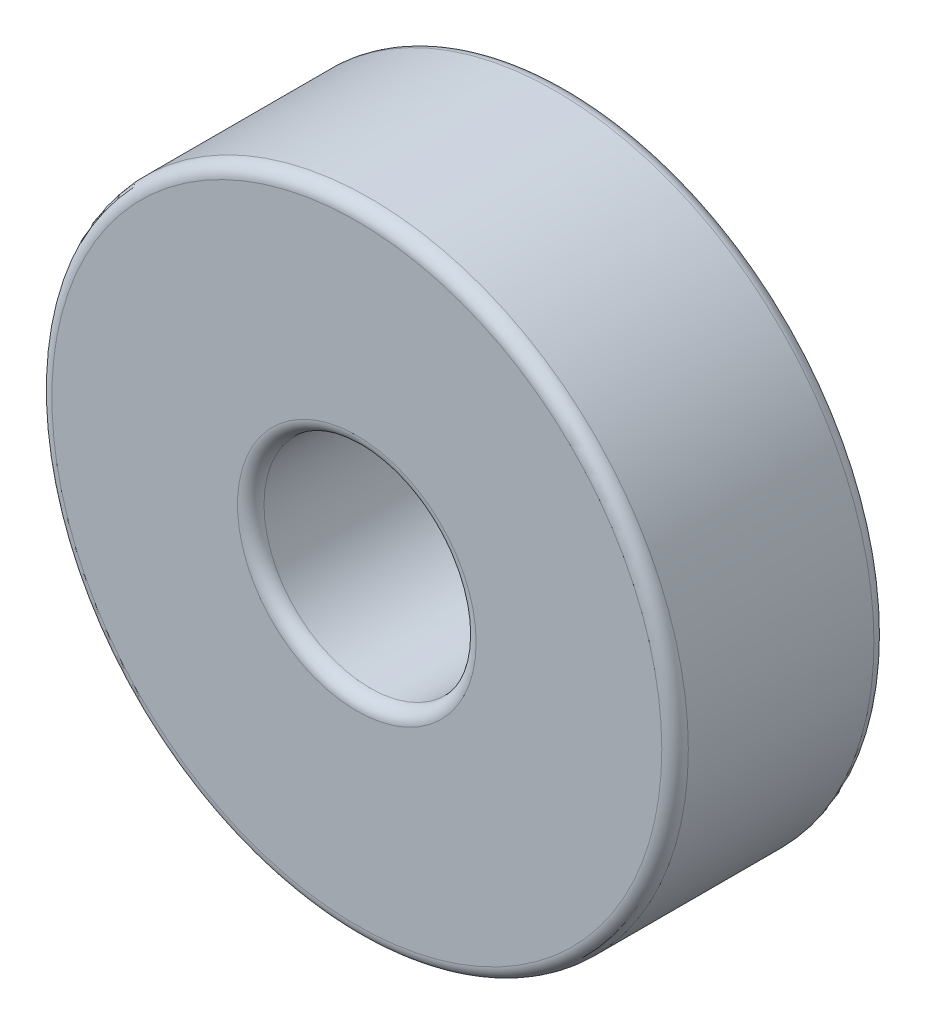
SolidWorks part; units mm, degrees
ref_plane "Alzado" through (0, 0, 0) normal (0, 0, 1) x (1, 0, 0)
ref_plane "Planta" through (0, 0, 0) normal (0, 1, 0) x (1, 0, 0)
ref_plane "Vista lateral" through (0, 0, 0) normal (1, 0, 0) x (0, 0, -1)
sketch "Croquis1" plane through (0, 0, 0) normal (0, 0, 1) x (1, 0, 0)
  circle A0 centre (0, 0) radius 4
  circle A1 centre (0, 0) radius 12
  dimension "D1" = 8
  dimension "D2" = 24
extrude "Saliente-Extruir1" add sketch "Croquis1" along normal blind 8
fillet "Redondeo1" radius 0.5 4 edges at (4, 0, 8) (4, 0, 0) (12, 0, 0) (12, 0, 8)
